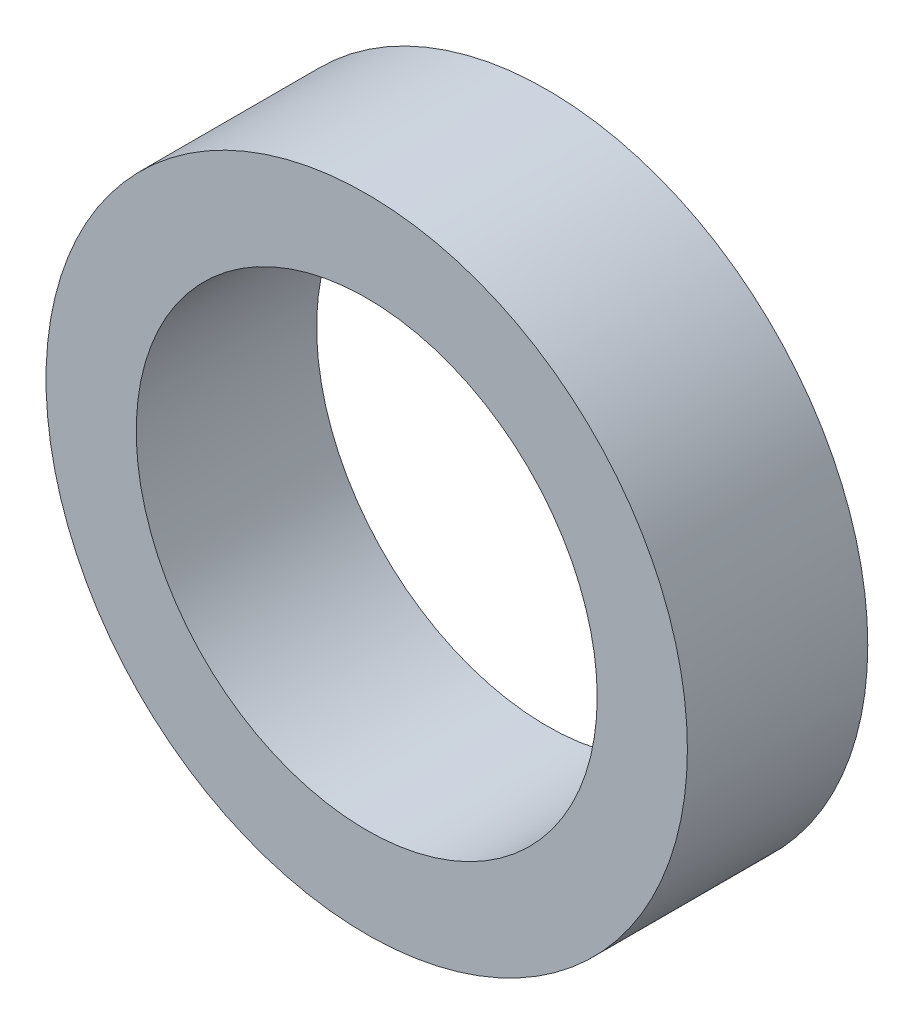
SolidWorks part; units mm, degrees
ref_plane "Alzado" through (0, 0, 0) normal (0, 0, 1) x (1, 0, 0)
ref_plane "Planta" through (0, 0, 0) normal (0, 1, 0) x (1, 0, 0)
ref_plane "Vista lateral" through (0, 0, 0) normal (1, 0, 0) x (0, 0, -1)
sketch "Croquis1" plane through (0, 0, 0) normal (0, 0, 1) x (1, 0, 0)
  circle A0 centre (0, 0) radius 16
  circle A1 centre (0, 0) radius 11.5
extrude "Saliente-Extruir1" add sketch "Croquis1" along normal blind 9
